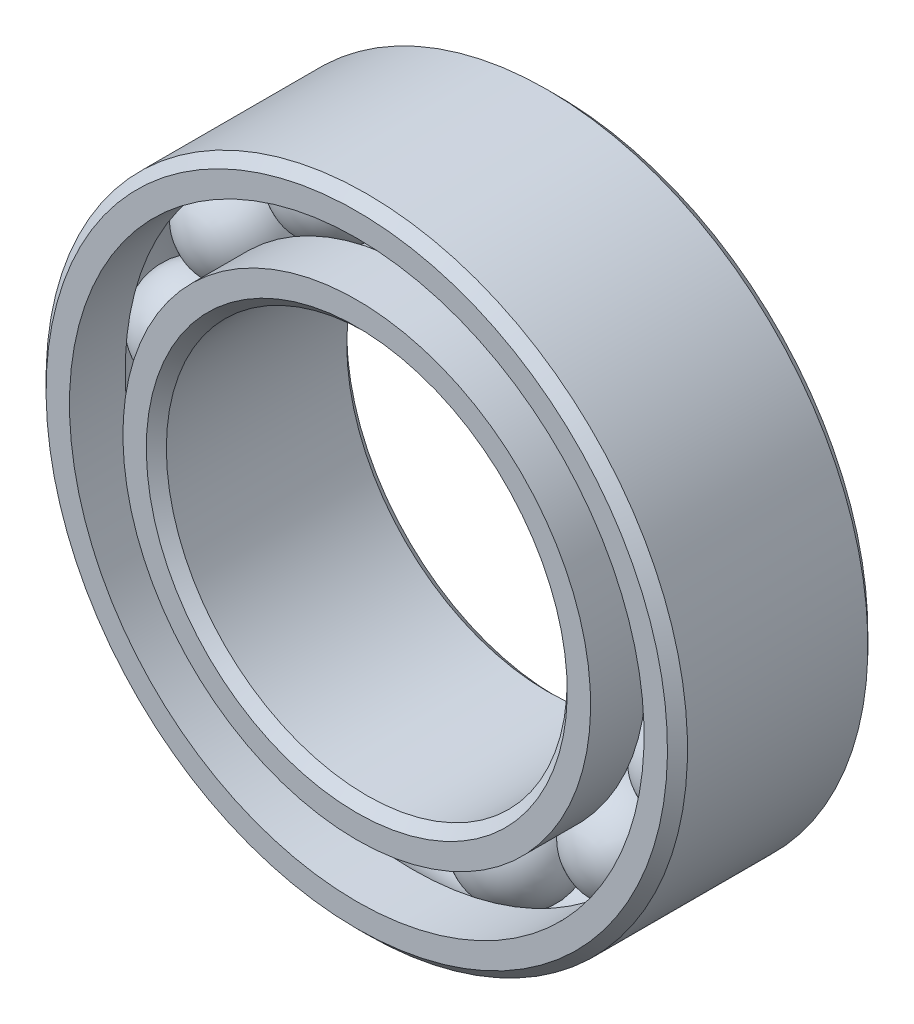
SolidWorks part; units mm, degrees
ref_plane "Front Plane" through (0, 0, 0) normal (0, 0, 1) x (1, 0, 0)
ref_plane "Top Plane" through (0, 0, 0) normal (0, 1, 0) x (1, 0, 0)
ref_plane "Right Plane" through (0, 0, 0) normal (1, 0, 0) x (0, 0, -1)
sketch "Sketch1" plane through (0, 0, 0) normal (0, 0, 1) x (1, 0, 0)
  circle A0 centre (0, 0) radius 16
  circle A1 centre (0, 0) radius 10
  dimension "OD" = 32
  dimension "ID" = 20
  dimension "For Shaft Diameter" = 20
  dimension "For Housing ID" = 32
sketch "Sketch5" plane through (0, 0, 0) normal (1, 0, 0) x (0, 0, -1)
  line L0 (-5, 0) -> (5, 0) construction
  line L1 (0, 16) -> (0, -16) construction
  line L2 (4.5, 16) -> (-4.5, 16)
  line L3 (-4.5, 16) -> (-5, 15.5)
  line L4 (-5, 15.5) -> (-5, 14.3333)
  line L5 (-5, 14.3333) -> (-2.2222, 14.3333)
  line L6 (5, 14.3333) -> (2.2222, 14.3333)
  line L7 (5, 15.5) -> (5, 14.3333)
  line L8 (4.5, 16) -> (5, 15.5)
  line L9 (0, 16) -> (0, 13) construction
  line L10 (0, 13) -> (0, 10) construction
  line L11 (-2.5915, 13) -> (-5, 13) construction
  line L12 (3.6053, 11.6921) -> (3.9863, 11.6921) construction
  line L13 (-3.6053, 11.6921) -> (-3.9863, 11.6921) construction
  line L14 (-3.6053, 11.6921) -> (-3.6053, 14.3079) construction
  line L15 (-3.6053, 14.3079) -> (-3.9863, 14.3079) construction
  line L16 (-3.9863, 11.6921) -> (-3.9863, 14.3079) construction
  line L17 (-3.6053, 11.6921) -> (-3.9863, 14.3079) construction
  line L18 (-3.6053, 14.3079) -> (-3.9863, 11.6921) construction
  line L19 (3.9863, 11.6921) -> (3.9863, 14.3079) construction
  line L20 (3.6053, 14.3079) -> (3.9863, 14.3079) construction
  line L21 (3.6053, 11.6921) -> (3.6053, 14.3079) construction
  line L22 (0, 16) -> (0, -16) construction
  arc A0 (-2.2222, 14.3333) -> (2.2222, 14.3333) centre (0, 13) cw
  circle A1 centre (0, 13) radius 2.5915 construction
  point P14 (0, 10)
  point P15 (-3.7958, 13)
  dimension "D1" = 45
  dimension "D2" = 0.5
  dimension "D3" = 4.4444
  dimension "D4" = 1.3333
  dimension "D5" = 0.381
  dimension "D6" = 0.0254
  dimension "Width" = 10
sketch "Sketch6" plane through (0, 0, 0) normal (1, 0, 0) x (0, 0, -1)
  line L0 (4.5, 16) -> (5, 15.5) construction
  line L1 (5, 15.5) -> (5, 14.3333) construction
  line L2 (5, 14.3333) -> (2.2222, 14.3333) construction
  line L3 (-5, 14.3333) -> (-2.2222, 14.3333) construction
  line L4 (-5, 15.5) -> (-5, 14.3333) construction
  line L5 (-4.5, 16) -> (-5, 15.5) construction
  line L6 (4.5, 16) -> (-4.5, 16) construction
  line L7 (4.5, 16) -> (5, 15.5)
  line L8 (5, 15.5) -> (5, 14.3333)
  line L9 (5, 14.3333) -> (2.2222, 14.3333)
  line L10 (-5, 14.3333) -> (-2.2222, 14.3333)
  line L11 (-5, 15.5) -> (-5, 14.3333)
  line L12 (-4.5, 16) -> (-5, 15.5)
  line L13 (4.5, 16) -> (-4.5, 16)
  arc A0 (2.2222, 14.3333) -> (-2.2222, 14.3333) centre (0, 13) ccw construction
  arc A1 (2.2222, 14.3333) -> (-2.2222, 14.3333) centre (0, 13) ccw
revolve "Revolve5" add sketch "Sketch6" angle 360 about L0
sketch "Sketch3" plane through (0, 0, 0) normal (1, 0, 0) x (0, 0, -1)
  line L0 (-5, 11.6667) -> (-2.2222, 11.6667)
  line L1 (0, 16) -> (0, -16) construction
  line L2 (-5, 15.5) -> (-5, 14.3333) construction
  line L3 (-5, 11.6667) -> (-5, 10.5)
  line L4 (-4.5, 16) -> (-5, 15.5) construction
  line L5 (-5, 10.5) -> (-4.5, 10)
  line L6 (-4.5, 10) -> (4.5, 10)
  line L8 (4.5, 10) -> (5, 10.5)
  line L10 (5, 10.5) -> (5, 11.6667)
  line L11 (5, 11.6667) -> (2.2222, 11.6667)
  line L12 (4.5, 16) -> (4.5, -16) construction
  line L13 (4.5, 16) -> (5, 15.5) construction
  line L14 (5, -15.5) -> (5, 15.5) construction
  arc A0 (2.2222, 14.3333) -> (-2.2222, 14.3333) centre (0, 13) ccw construction
  arc A1 (2.2222, 11.6667) -> (-2.2222, 11.6667) centre (0, 13) cw
revolve "Revolve3" add sketch "Sketch3" angle 360 about L0
sketch "Sketch4" plane through (0, 0, 0) normal (1, 0, 0) x (0, 0, -1)
  line L0 (-2.5915, 13) -> (2.5915, 13)
  arc A2 (-2.5915, 13) -> (2.5915, 13) centre (0, 13) cw
  arc A3 (2.2222, 14.3333) -> (-2.2222, 14.3333) centre (0, 13) ccw construction
revolve "Revolve4" add sketch "Sketch4" angle 360 about L0
pattern_circular "CirPattern1" count 13 over 360 about axis through (0, 0, 0) along (0, 0, 1) of bodies 104
equation "\"D2@Sketch5\" = \"Width@Sketch5\" * .05"
equation "\"D3@Sketch5\" = \"Width@Sketch5\" / 2.25"
equation "\"D4@Sketch5\"=((\"OD@Sketch1\"-\"ID@Sketch1\")/2)/4.5"
